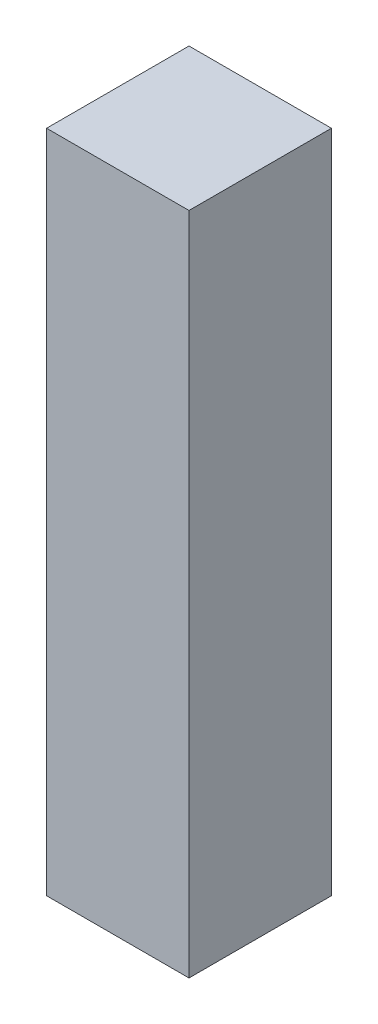
SolidWorks part; units mm, degrees
ref_plane "Front Plane" through (0, 0, 0) normal (0, 0, 1) x (1, 0, 0)
ref_plane "Top Plane" through (0, 0, 0) normal (0, 1, 0) x (1, 0, 0)
ref_plane "Right Plane" through (0, 0, 0) normal (1, 0, 0) x (0, 0, -1)
sketch "Sketch1" plane through (0, 0, 0) normal (0, 1, 0) x (1, 0, 0)
  line L1 (-123.8208, -13.4434) -> (26.1792, -13.4434)
  line L2 (-123.8208, -13.4434) -> (-123.8208, -163.4434)
  line L3 (-123.8208, -163.4434) -> (26.1792, -163.4434)
  line L4 (26.1792, -13.4434) -> (26.1792, -163.4434)
  dimension "D1" = 150
  dimension "D2" = 150
extrude "Boss-Extrude1" add sketch "Sketch1" along normal blind 700
